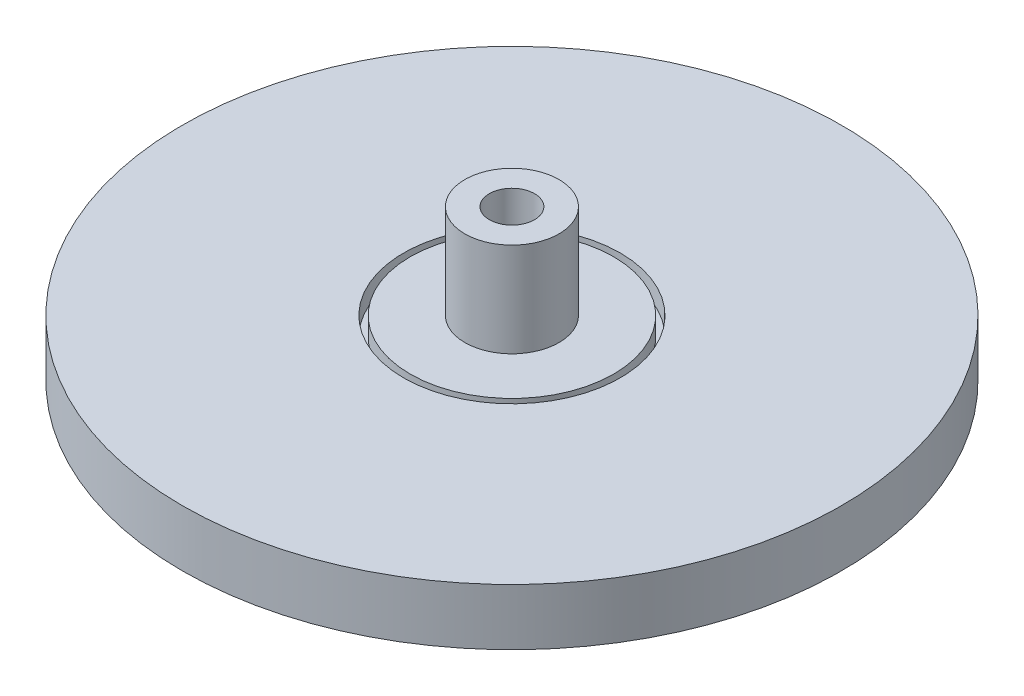
SolidWorks part; units mm, degrees
ref_plane "Front Plane" through (0, 0, 0) normal (0, 0, 1) x (1, 0, 0)
ref_plane "Top Plane" through (0, 0, 0) normal (0, 1, 0) x (1, 0, 0)
ref_plane "Right Plane" through (0, 0, 0) normal (1, 0, 0) x (0, 0, -1)
sketch "Sketch1" plane through (0, 0, 0) normal (0, 1, 0) x (1, 0, 0)
  circle A0 centre (0, 0) radius 175
extrude "Boss-Extrude1" add sketch "Sketch1" along normal blind 30
sketch "Sketch2" plane through (0, 30, 0) normal (0, 1, 0) x (1, 0, 0)
  circle A0 centre (0, 0) radius 25
  circle A1 centre (0, 0) radius 12
extrude "Boss-Extrude2" add sketch "Sketch2" along normal blind 50
sketch "Sketch3" plane through (0, 30, 0) normal (0, 1, 0) x (1, 0, 0)
  circle A0 centre (0, 0) radius 57.5
  circle A1 centre (0, 0) radius 54
extrude "Cut-Extrude1" cut sketch "Sketch3" against normal blind 10
